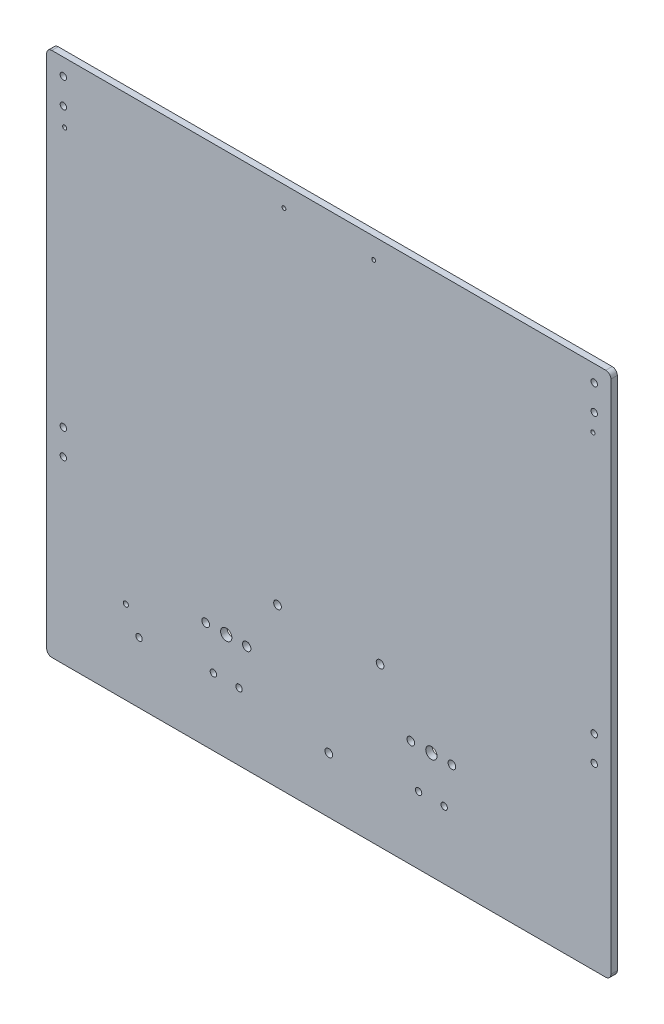
SolidWorks part; units mm, degrees
ref_plane "Front Plane" through (0, 0, 0) normal (0, 0, 1) x (1, 0, 0)
ref_plane "Top Plane" through (0, 0, 0) normal (0, 1, 0) x (1, 0, 0)
ref_plane "Right Plane" through (0, 0, 0) normal (1, 0, 0) x (0, 0, -1)
ref_plane "Plane1" through (0, 0, 0) normal (0, 0, -1) x (-1, 0, 0)
sketch "Sketch1" plane through (0, 0, 0) normal (0, 0, -1) x (-1, 0, 0)
  line L0 (-134.3266, -194.3013) -> (285.6734, -194.3013)
  line L1 (295.6734, -184.3013) -> (295.6734, 205.6987)
  line L2 (285.6734, 215.6987) -> (-134.3266, 215.6987)
  line L3 (-144.3266, 205.6987) -> (-144.3266, -184.3013)
  arc A0 (285.6734, -194.3013) -> (295.6734, -184.3013) centre (285.6734, -184.3013) ccw
  arc A1 (295.6734, 205.6987) -> (285.6734, 215.6987) centre (285.6734, 205.6987) ccw
  arc A2 (-134.3266, 215.6987) -> (-144.3266, 205.6987) centre (-134.3266, 205.6987) ccw
  arc A3 (-144.3266, -184.3013) -> (-134.3266, -194.3013) centre (-134.3266, -184.3013) ccw
  circle A4 centre (282.6734, 202.6987) radius 2.5
  circle A5 centre (282.6734, 182.6987) radius 2.5
  circle A6 centre (282.6734, -34.3013) radius 2.5
  circle A7 centre (282.6734, -54.3013) radius 2.5
  circle A8 centre (-131.3266, 202.6987) radius 2.5
  circle A9 centre (-131.3266, 182.6987) radius 2.5
  circle A10 centre (-131.3266, -34.3013) radius 2.5
  circle A11 centre (-131.3266, -54.3013) radius 2.5
  circle A12 centre (165.6734, -141.8013) radius 2.5
  circle A13 centre (145.6734, -141.8013) radius 2.5
  circle A14 centre (5.6734, -141.8013) radius 2.5
  circle A15 centre (-14.3266, -141.8013) radius 2.5
  circle A16 centre (-4.3266, -110.8013) radius 4.4
  circle A17 centre (155.6734, -110.8013) radius 4.4
  circle A18 centre (171.6734, -110.8013) radius 3
  circle A19 centre (139.6734, -110.8013) radius 3.2791
  circle A20 centre (11.6734, -110.8013) radius 3
  circle A21 centre (-20.3266, -110.8013) radius 3
  circle A22 centre (75.6734, -150.8013) radius 3
  circle A23 centre (35.6734, -70.8013) radius 3
  circle A24 centre (115.6734, -70.8013) radius 3
  circle A25 centre (281.6734, 168.6987) radius 1.6
  circle A26 centre (-130.3266, 168.6987) radius 1.6
  circle A27 centre (223.6734, -146.7423) radius 2.5
  dimension "D3" = 43.5
  dimension "D4" = 10
  dimension "D9" = 13
  dimension "D10" = 13
  dimension "D11" = 13
  dimension "D12" = 14
  dimension "D13" = 47
  dimension "D14" = 47
  dimension "D15" = 14
  dimension "D16" = 3.2
  dimension "D17" = 3.2
  dimension "D18" = 123.5
  dimension "D19" = 6
  dimension "D20" = 123.5
  dimension "D21" = 6
  dimension "D22" = 5
  dimension "D1" = 180
  dimension "D2" = 180
  dimension "D5" = 420
  dimension "D6" = 390
  dimension "D7" = 420
  dimension "D8" = 390
extrude "Boss-Extrude1" add sketch "Sketch1" against normal blind 5
sketch "Sketch2" plane through (0, 0, 0) normal (0, 0, -1) x (-1, 0, 0)
  line L0 (75.6734, 215.6987) -> (75.6734, -194.3013) construction
  line L1 (-144.3266, 205.6987) -> (-134.3266, 205.6987)
  line L2 (-144.3266, 205.6987) -> (-144.3266, 211.6987)
  line L3 (-140.3266, 215.6987) -> (-134.3266, 215.6987)
  line L4 (-134.3266, 205.6987) -> (-134.3266, 215.6987)
  line L5 (75.6734, 10.6987) -> (-144.3266, 10.6987) construction
  line L6 (285.6734, 205.6987) -> (285.6734, 215.6987)
  line L7 (291.6734, 215.6987) -> (285.6734, 215.6987)
  line L8 (295.6734, 205.6987) -> (295.6734, 211.6987)
  line L9 (295.6734, 205.6987) -> (285.6734, 205.6987)
  line L10 (295.6734, -184.3013) -> (285.6734, -184.3013)
  line L11 (295.6734, -184.3013) -> (295.6734, -190.3013)
  line L12 (291.6734, -194.3013) -> (285.6734, -194.3013)
  line L13 (285.6734, -184.3013) -> (285.6734, -194.3013)
  line L14 (-134.3266, -184.3013) -> (-134.3266, -194.3013)
  line L15 (-140.3266, -194.3013) -> (-134.3266, -194.3013)
  line L16 (-144.3266, -184.3013) -> (-144.3266, -190.3013)
  line L17 (-144.3266, -184.3013) -> (-134.3266, -184.3013)
  arc A0 (-144.3266, 211.6987) -> (-140.3266, 215.6987) centre (-140.3266, 211.6987) cw
  arc A1 (295.6734, 211.6987) -> (291.6734, 215.6987) centre (291.6734, 211.6987) ccw
  arc A2 (295.6734, -190.3013) -> (291.6734, -194.3013) centre (291.6734, -190.3013) cw
  arc A3 (-144.3266, -190.3013) -> (-140.3266, -194.3013) centre (-140.3266, -190.3013) ccw
sketch "Sketch5" plane through (0, 0, 0) normal (0, 0, -1) x (-1, 0, 0)
  line L0 (75.6734, 215.6987) -> (75.6734, 169.5281) construction
  line L1 (285.6734, 215.6987) -> (-134.3266, 215.6987) construction
  circle A2 centre (40.6734, 199.6987) radius 1.5
  circle A3 centre (110.6734, 199.6987) radius 1.5
  dimension "D2" = 3
  dimension "D3" = 3
  dimension "D1" = 70
  dimension "28" = 16
sketch "Sketch7" plane through (0, 0, 5) normal (0, 0, 1) x (1, 0, 0)
  line L0 (-295.6734, -184.3013) -> (-295.6734, 205.6987) construction
  line L1 (134.3266, -194.3013) -> (-285.6734, -194.3013) construction
  circle A0 centre (-233.9438, -129.3749) radius 2
  dimension "D1" = 61.7296
  dimension "D2" = 64.9264
  dimension "D3" = 4
extrude "Cut-Extrude1" cut sketch "Sketch5" against normal blind 10
extrude "Boss-Extrude2" add sketch "Sketch2" against normal up to vertex (5 mm away)
extrude "Cut-Extrude2" cut sketch "Sketch7" against normal blind 10
